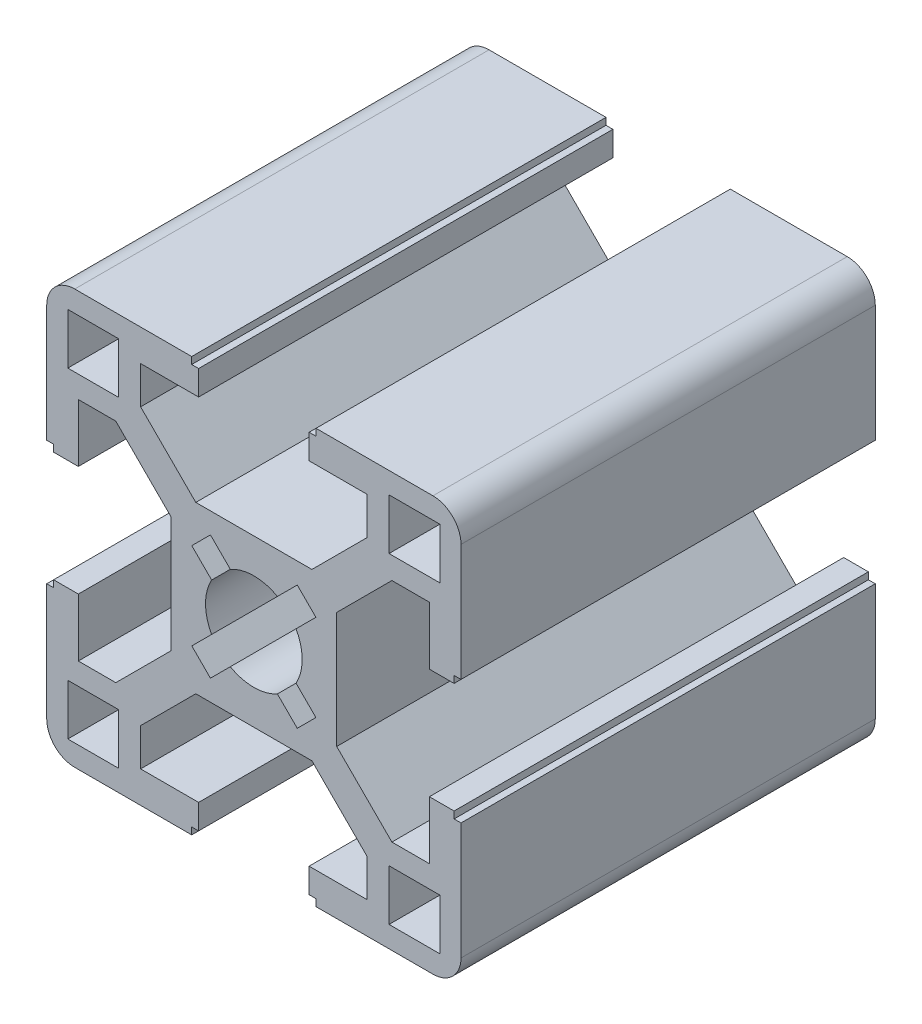
SolidWorks part; units mm, degrees
ref_plane "Front Plane" through (0, 0, 0) normal (0, 0, 1) x (1, 0, 0)
ref_plane "Top Plane" through (0, 0, 0) normal (0, 1, 0) x (1, 0, 0)
ref_plane "Right Plane" through (0, 0, 0) normal (1, 0, 0) x (0, 0, -1)
sketch "Sketch1" plane through (0, 0, 0) normal (0, 0, 1) x (1, 0, 0)
  line L0 (-15, 0) -> (15, 0) construction
  line L1 (0, -15) -> (0, 15) construction
  line L2 (-4.5, 15) -> (4.5, 15) construction
  line L3 (-4, -15) -> (4, -15) construction
  line L4 (-4.5, 15) -> (-4.5, 14.5)
  line L5 (-4.5, 14.5) -> (-4, 14.5)
  line L6 (-4, 14.5) -> (-4, 12.71)
  line L7 (-4, 12.71) -> (-8.2, 12.71)
  line L8 (-8.2, 12.71) -> (-8.2, 9.9961)
  line L9 (-8.2, 9.9961) -> (-4.2039, 6)
  line L10 (-4.2039, 6) -> (0, 6)
  line L11 (0, 0) -> (-15, 15) construction
  line L12 (-4.5, 15) -> (-12.968, 15)
  line L13 (-4.4937, 3.1431) -> (-3.1431, 4.4937)
  line L14 (-13.47, 9.79) -> (-9.79, 9.79)
  line L15 (-13.47, 9.79) -> (-13.47, 13.47)
  line L16 (-13.47, 13.47) -> (-9.79, 13.47)
  line L17 (-9.79, 9.79) -> (-9.79, 13.47)
  line L18 (-13.47, 9.79) -> (-9.79, 13.47) construction
  line L19 (-13.47, 13.47) -> (-9.79, 9.79) construction
  line L20 (-3.1431, 4.4937) -> (-1.7057, 3.0563)
  line L21 (-4.4937, 3.1431) -> (-3.0563, 1.7057)
  line L22 (-6, 4.2039) -> (-6, 0)
  line L23 (-9.9961, 8.2) -> (-6, 4.2039)
  line L24 (-15, 4.5) -> (-15, 12.968)
  line L25 (-12.71, 8.2) -> (-9.9961, 8.2)
  line L26 (-12.71, 4) -> (-12.71, 8.2)
  line L27 (-14.5, 4) -> (-12.71, 4)
  line L28 (-14.5, 4.5) -> (-14.5, 4)
  line L29 (-15, 4.5) -> (-14.5, 4.5)
  circle A0 centre (0, 0) radius 3.5
  arc A1 (-12.968, 15) -> (-15, 12.968) centre (-12.968, 12.968) ccw
  point P4 (0, 0)
  point P8 (0, 0)
  point P13 (0, 15)
  point P15 (0, -15)
  point P16 (0, 6)
  point P23 (-11.63, 11.63)
  point P26 (0, 6)
  point P33 (-3.8184, 3.8184)
  dimension "Center Hole Diameter" = 7
  dimension "D11" = 2.032
  dimension "Rail Height" = 30
  dimension "Rail Width" = 30
  dimension "T-Slot Width" = 8
  dimension "T-Slot Depth" = 9
  dimension "D1" = 9
  dimension "D2" = 45
  dimension "D3" = 8
  dimension "D4" = 2.29
  dimension "D5" = 16.4
  dimension "D7" = 2.54
  dimension "D6" = 3.37
  dimension "D8" = 3.68
  dimension "D9" = 5.4
  dimension "D10" = 1.91
sketch "Sketch2" plane through (0, 0, 0) normal (1, 0, 0) x (0, 0, -1)
  line L0 (-1219.2, 0) -> (1219.2, 0) construction
  line L2 (0, -15) -> (0, 15) construction
  line L3 (0, -15) -> (0, 15) construction
  line L4 (-1219.2, -15) -> (-1219.2, 15) construction
  line L5 (1219.2, -15) -> (1219.2, 15) construction
  point P0 (-1181.7, 0)
  point P3 (0, 0)
  point P4 (1181.7, 0)
  point P12 (-1219.2, 0)
  point P14 (1219.2, 0)
  dimension "Length" = 2438.4
  dimension "D1" = 37.5
sketch "Sketch3" plane through (0, 0, 0) normal (0, 0, 1) x (1, 0, 0)
  line L0 (-3.1431, 4.4937) -> (-1.7057, 3.0563) construction
  line L1 (-4.4937, 3.1431) -> (-3.1431, 4.4937) construction
  line L2 (-4.4937, 3.1431) -> (-3.0563, 1.7057) construction
  line L4 (-13.47, 9.79) -> (-9.79, 9.79)
  line L5 (-9.79, 9.79) -> (-9.79, 13.47)
  line L6 (-9.79, 13.47) -> (-13.47, 13.47)
  line L7 (-13.47, 13.47) -> (-13.47, 9.79)
  line L8 (-13.47, 9.79) -> (-9.79, 9.79)
  line L9 (-9.79, 9.79) -> (-9.79, 13.47)
  line L10 (-9.79, 13.47) -> (-13.47, 13.47)
  line L11 (-13.47, 13.47) -> (-13.47, 9.79)
  line L12 (-4.2039, 6) -> (0, 6) construction
  line L13 (-8.2, 9.9961) -> (-4.2039, 6) construction
  line L14 (-8.2, 12.71) -> (-8.2, 9.9961) construction
  line L15 (-4, 12.71) -> (-8.2, 12.71) construction
  line L16 (-4, 14.5) -> (-4, 12.71) construction
  line L17 (-4.5, 14.5) -> (-4, 14.5) construction
  line L18 (-4.5, 15) -> (-4.5, 14.5) construction
  line L19 (-4.5, 15) -> (-12.968, 15) construction
  line L20 (-15, 4.5) -> (-15, 12.968) construction
  line L21 (-15, 4.5) -> (-14.5, 4.5) construction
  line L22 (-14.5, 4.5) -> (-14.5, 4) construction
  line L23 (-14.5, 4) -> (-12.71, 4) construction
  line L24 (-12.71, 4) -> (-12.71, 8.2) construction
  line L25 (-12.71, 8.2) -> (-9.9961, 8.2) construction
  line L26 (-9.9961, 8.2) -> (-6, 4.2039) construction
  line L27 (-6, 4.2039) -> (-6, 0) construction
  line L28 (-3.1431, 4.4937) -> (-1.7057, 3.0563)
  line L29 (-4.4937, 3.1431) -> (-3.1431, 4.4937)
  line L30 (-4.4937, 3.1431) -> (-3.0563, 1.7057)
  line L32 (-4.2039, 6) -> (0, 6)
  line L33 (-8.2, 9.9961) -> (-4.2039, 6)
  line L34 (-8.2, 12.71) -> (-8.2, 9.9961)
  line L35 (-4, 12.71) -> (-8.2, 12.71)
  line L36 (-4, 14.5) -> (-4, 12.71)
  line L37 (-4.5, 14.5) -> (-4, 14.5)
  line L38 (-4.5, 15) -> (-4.5, 14.5)
  line L39 (-4.5, 15) -> (-12.968, 15)
  line L40 (-15, 4.5) -> (-15, 12.968)
  line L41 (-15, 4.5) -> (-14.5, 4.5)
  line L42 (-14.5, 4.5) -> (-14.5, 4)
  line L43 (-14.5, 4) -> (-12.71, 4)
  line L44 (-12.71, 4) -> (-12.71, 8.2)
  line L45 (-12.71, 8.2) -> (-9.9961, 8.2)
  line L46 (-9.9961, 8.2) -> (-6, 4.2039)
  line L47 (-6, 4.2039) -> (-6, 0)
  line L48 (9.79, 13.47) -> (9.79, 9.79)
  line L49 (9.79, 9.79) -> (13.47, 9.79)
  line L50 (13.47, 9.79) -> (13.47, 13.47)
  line L51 (13.47, 13.47) -> (9.79, 13.47)
  line L52 (4.4937, 3.1431) -> (3.0563, 1.7057)
  line L53 (3.1431, 4.4937) -> (4.4937, 3.1431)
  line L54 (3.1431, 4.4937) -> (1.7057, 3.0563)
  line L55 (6, 4.2039) -> (6, 0)
  line L56 (9.9961, 8.2) -> (6, 4.2039)
  line L57 (12.71, 8.2) -> (9.9961, 8.2)
  line L58 (12.71, 4) -> (12.71, 8.2)
  line L59 (14.5, 4) -> (12.71, 4)
  line L60 (14.5, 4.5) -> (14.5, 4)
  line L61 (15, 4.5) -> (14.5, 4.5)
  line L62 (15, 4.5) -> (15, 12.968)
  line L63 (4.5, 15) -> (12.968, 15)
  line L64 (4.5, 15) -> (4.5, 14.5)
  line L65 (4.5, 14.5) -> (4, 14.5)
  line L66 (4, 14.5) -> (4, 12.71)
  line L67 (4, 12.71) -> (8.2, 12.71)
  line L68 (8.2, 12.71) -> (8.2, 9.9961)
  line L69 (8.2, 9.9961) -> (4.2039, 6)
  line L70 (4.2039, 6) -> (0, 6)
  line L71 (13.47, -9.79) -> (9.79, -9.79)
  line L72 (9.79, -9.79) -> (9.79, -13.47)
  line L73 (9.79, -13.47) -> (13.47, -13.47)
  line L74 (13.47, -13.47) -> (13.47, -9.79)
  line L75 (3.1431, -4.4937) -> (1.7057, -3.0563)
  line L76 (4.4937, -3.1431) -> (3.1431, -4.4937)
  line L77 (4.4937, -3.1431) -> (3.0563, -1.7057)
  line L78 (4.2039, -6) -> (0, -6)
  line L79 (8.2, -9.9961) -> (4.2039, -6)
  line L80 (8.2, -12.71) -> (8.2, -9.9961)
  line L81 (4, -12.71) -> (8.2, -12.71)
  line L82 (4, -14.5) -> (4, -12.71)
  line L83 (4.5, -14.5) -> (4, -14.5)
  line L84 (4.5, -15) -> (4.5, -14.5)
  line L85 (4.5, -15) -> (12.968, -15)
  line L86 (15, -4.5) -> (15, -12.968)
  line L87 (15, -4.5) -> (14.5, -4.5)
  line L88 (14.5, -4.5) -> (14.5, -4)
  line L89 (14.5, -4) -> (12.71, -4)
  line L90 (12.71, -4) -> (12.71, -8.2)
  line L91 (12.71, -8.2) -> (9.9961, -8.2)
  line L92 (9.9961, -8.2) -> (6, -4.2039)
  line L93 (6, -4.2039) -> (6, 0)
  line L94 (-9.79, -13.47) -> (-9.79, -9.79)
  line L95 (-9.79, -9.79) -> (-13.47, -9.79)
  line L96 (-13.47, -9.79) -> (-13.47, -13.47)
  line L97 (-13.47, -13.47) -> (-9.79, -13.47)
  line L98 (-4.4937, -3.1431) -> (-3.0563, -1.7057)
  line L99 (-3.1431, -4.4937) -> (-4.4937, -3.1431)
  line L100 (-3.1431, -4.4937) -> (-1.7057, -3.0563)
  line L101 (-6, -4.2039) -> (-6, 0)
  line L102 (-9.9961, -8.2) -> (-6, -4.2039)
  line L103 (-12.71, -8.2) -> (-9.9961, -8.2)
  line L104 (-12.71, -4) -> (-12.71, -8.2)
  line L105 (-14.5, -4) -> (-12.71, -4)
  line L106 (-14.5, -4.5) -> (-14.5, -4)
  line L107 (-15, -4.5) -> (-14.5, -4.5)
  line L108 (-15, -4.5) -> (-15, -12.968)
  line L109 (-4.5, -15) -> (-12.968, -15)
  line L110 (-4.5, -15) -> (-4.5, -14.5)
  line L111 (-4.5, -14.5) -> (-4, -14.5)
  line L112 (-4, -14.5) -> (-4, -12.71)
  line L113 (-4, -12.71) -> (-8.2, -12.71)
  line L114 (-8.2, -12.71) -> (-8.2, -9.9961)
  line L115 (-8.2, -9.9961) -> (-4.2039, -6)
  line L116 (-4.2039, -6) -> (0, -6)
  arc A0 (-12.968, 15) -> (-15, 12.968) centre (-12.968, 12.968) ccw construction
  circle A1 centre (0, 0) radius 3.5
  arc A2 (-3.0563, 1.7057) -> (-3.0563, -1.7057) centre (0, 0) ccw
  arc A3 (-12.968, 15) -> (-15, 12.968) centre (-12.968, 12.968) ccw
  arc A4 (15, 12.968) -> (12.968, 15) centre (12.968, 12.968) ccw
  arc A5 (12.968, -15) -> (15, -12.968) centre (12.968, -12.968) ccw
  arc A6 (-15, -12.968) -> (-12.968, -15) centre (-12.968, -12.968) ccw
  arc A7 (1.7057, 3.0563) -> (-1.7057, 3.0563) centre (0, 0) ccw
  arc A8 (3.0563, -1.7057) -> (3.0563, 1.7057) centre (0, 0) ccw
  arc A9 (-1.7057, -3.0563) -> (1.7057, -3.0563) centre (0, 0) ccw
  point P116 (0, 0)
  dimension "D1" = 0
  dimension "D2" = 0
  dimension "D3" = 4
extrude "Boss-Extrude1" add sketch "Sketch3" along normal mid plane 2438.4
sketch "Sketch4" plane through (0, 15, 0) normal (0, 1, 0) x (1, 0, 0)
  line L0 (15, -1219.2) -> (15, 1219.2) construction
  line L1 (-15, 1219.2) -> (15, 1219.2)
  line L2 (-15, 1219.2) -> (-15, -1189.2)
  line L3 (-15, -1189.2) -> (15, -1189.2)
  line L4 (15, 1219.2) -> (15, -1189.2)
  line L5 (12.968, -1219.2) -> (4.5, -1219.2) construction
  dimension "D1" = 30
extrude "Cut-Extrude1" cut sketch "Sketch4" against normal through all
equation "\"D1@Sketch2\" = \"Rail Height@Sketch1\" * 1.25"
equation "\"D1@Sketch1\"=\"T-Slot Width@Sketch1\"+1mm"
equation "\"D3@Sketch1\"=\"T-Slot Width@Sketch1\""
equation "\"D1@Boss-Extrude1\"=\"Length@Sketch2\""
